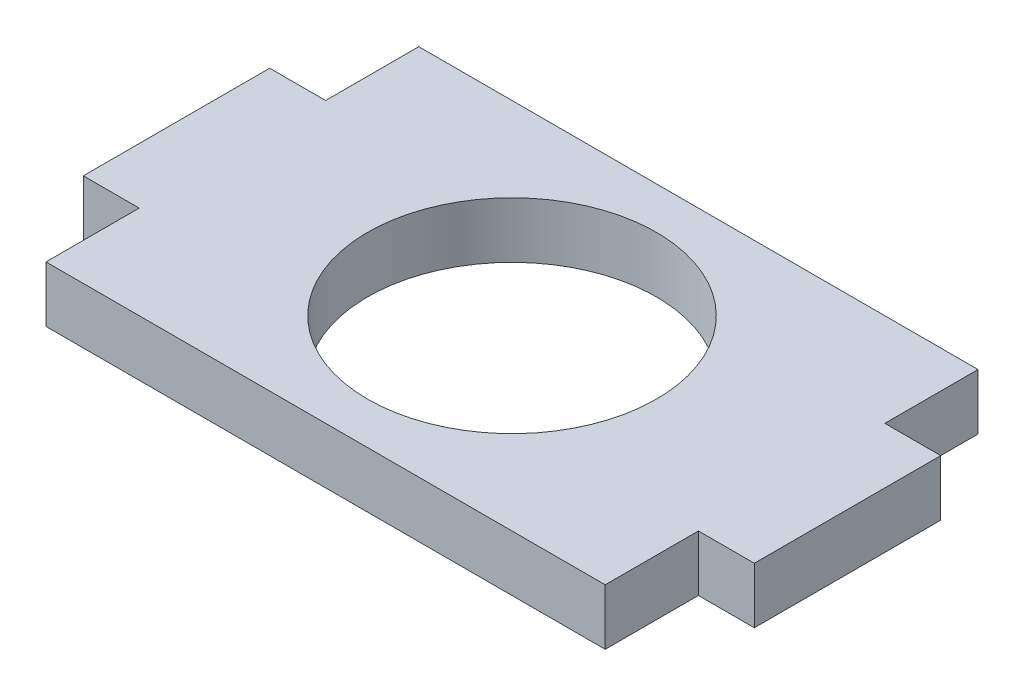
SolidWorks part; units mm, degrees
ref_plane "Alzado" through (0, 0, 0) normal (0, 0, 1) x (1, 0, 0)
ref_plane "Planta" through (0, 0, 0) normal (0, 1, 0) x (1, 0, 0)
ref_plane "Vista lateral" through (0, 0, 0) normal (1, 0, 0) x (0, 0, -1)
sketch "Croquis1" plane through (0, 0, 0) normal (0, 1, 0) x (1, 0, 0)
  line L0 (0, -5) -> (0, 5)
  line L1 (0, 5) -> (3, 5)
  line L2 (3, 5) -> (3, 10)
  line L3 (3, 10) -> (33, 10)
  line L5 (33, 5) -> (33, 10)
  line L6 (36, 5) -> (33, 5)
  line L7 (36, -5) -> (36, 5)
  line L9 (36, -5) -> (33, -5)
  line L10 (33, -5) -> (33, -10)
  line L12 (3, -10) -> (33, -10)
  line L13 (3, -5) -> (3, -10)
  line L14 (0, -5) -> (3, -5)
  circle A0 centre (18, 0) radius 7.75
  point P13 (36, 0)
  dimension "D1" = 15.5
  dimension "D2" = 3
  dimension "D3" = 5
  dimension "D4" = 30
extrude "Saliente-Extruir1" add sketch "Croquis1" along normal blind 3
